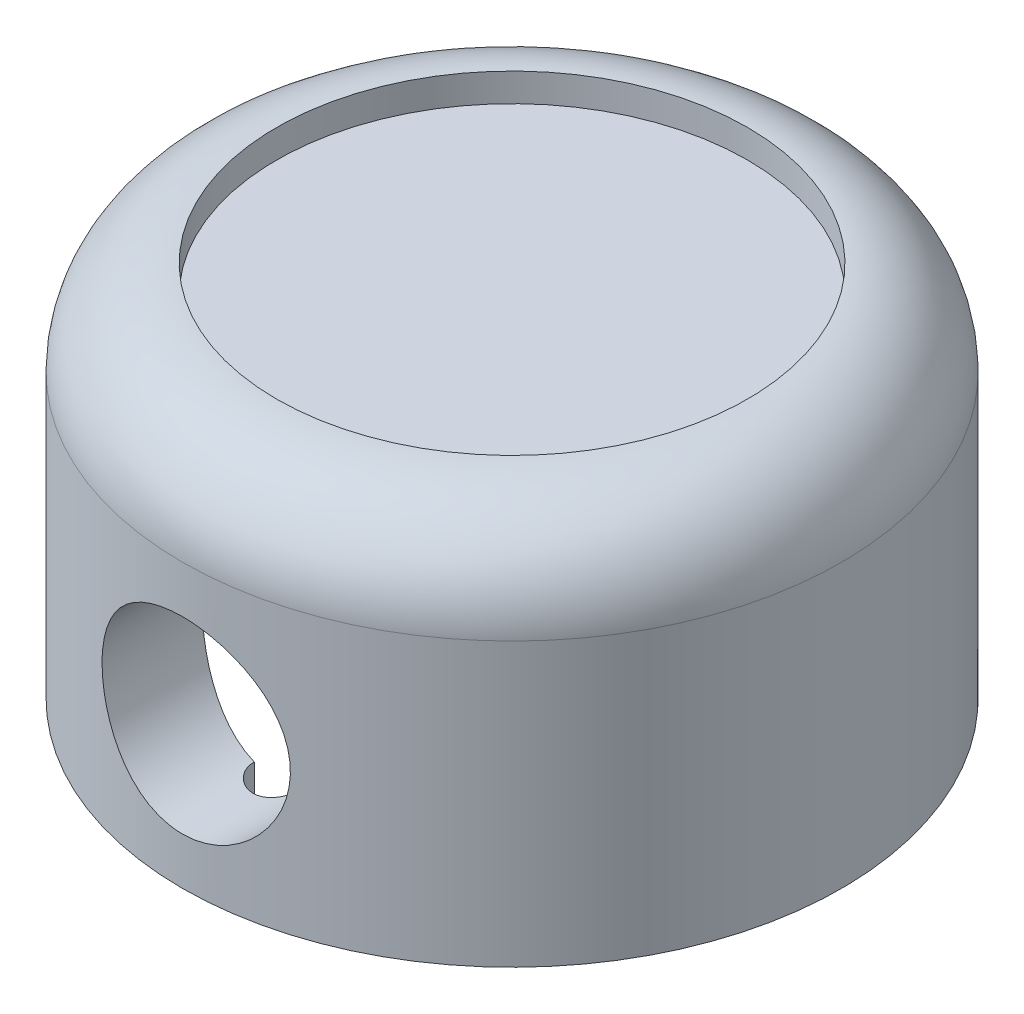
SolidWorks part; units mm, degrees
ref_plane "Plan de face" through (0, 0, 0) normal (0, 0, 1) x (1, 0, 0)
ref_plane "Plan de dessus" through (0, 0, 0) normal (0, 1, 0) x (1, 0, 0)
ref_plane "Plan de droite" through (0, 0, 0) normal (1, 0, 0) x (0, 0, -1)
sketch "Esquisse2" plane through (0, 0, 0) normal (0, 1, 0) x (1, 0, 0)
  circle A0 centre (0, 0) radius 35
extrude "Boss.-Extru.1" add sketch "Esquisse2" along normal blind 40 contours A0
fillet "Congé1" radius 10 1 edges at (0, 40, 35)
sketch "Esquisse3" plane through (0, 0, 0) normal (0, -1, 0) x (1, 0, 0)
  circle A0 centre (0, 0) radius 25
extrude "Enlèv. mat.-Extru.1" cut sketch "Esquisse3" against normal blind 30
sketch "Esquisse4" plane through (0, 0, 0) normal (0, -1, 0) x (1, 0, 0)
  line L0 (0, 0) -> (0, 25) construction
  circle A0 centre (0, 25) radius 2.5
sketch "Esquisse7" plane through (0, 40, 0) normal (0, 1, 0) x (1, 0, 0)
  circle A0 centre (0, 0) radius 25
extrude "Enlèv. mat.-Extru.3" cut sketch "Esquisse7" against normal blind 3
sketch "Esquisse8" plane through (0, 0, 0) normal (0, 0, 1) x (1, 0, 0)
  line L1 (0, 30) -> (0, 0) construction
  line L2 (-35, 30) -> (35, 30) construction
  circle A0 centre (0, 15) radius 10
extrude "Enlèv. mat.-Extru.4" cut sketch "Esquisse8" along normal blind 45
extrude "Enlèv. mat.-Extru.5" cut sketch "Esquisse4" against normal blind 30 contours A0
